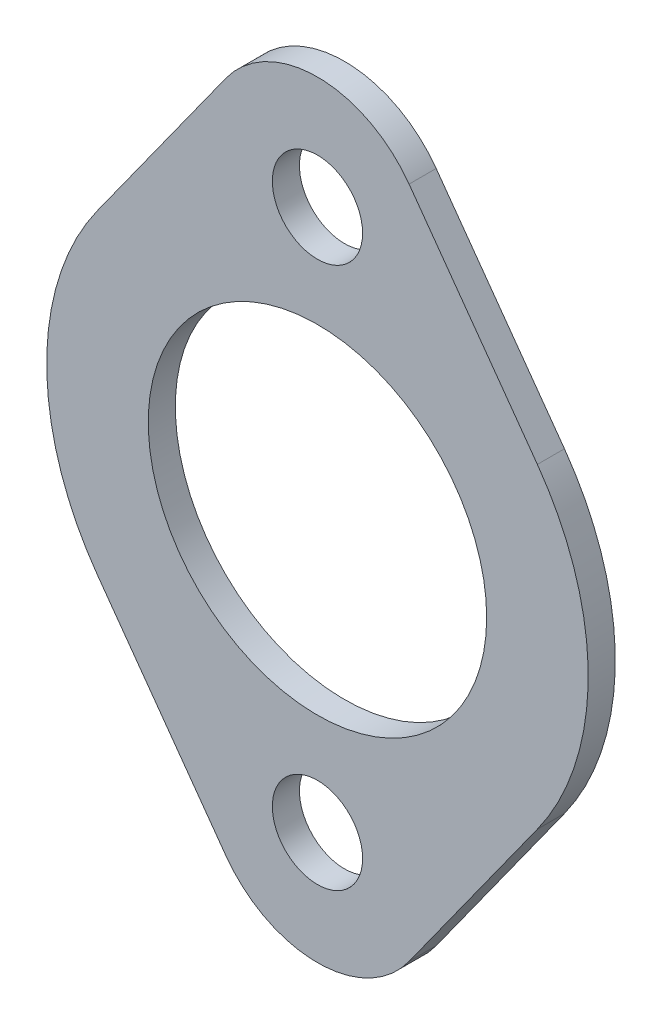
SolidWorks part; units mm, degrees
material "PW20:29:Sc:0:"
ref_plane "Front" through (0, 0, 0) normal (0, 0, 1) x (1, 0, 0)
ref_plane "Top" through (0, 0, 0) normal (0, 1, 0) x (1, 0, 0)
ref_plane "Right" through (0, 0, 0) normal (1, 0, 0) x (0, 0, -1)
sketch "Sketch1" plane through (0, 0, 0) normal (0, 0, 1) x (1, 0, 0)
  line L0 (0, 0) -> (0, 94.4945) construction
  line L1 (0, 0) -> (88.837, 0) construction
  line L2 (12.8942, 47.3604) -> (30.9461, 22.225)
  line L3 (12.8942, -47.3604) -> (30.9461, -22.225)
  line L4 (-12.8942, 47.3604) -> (-30.9461, 22.225)
  line L5 (-12.8942, -47.3604) -> (-30.9461, -22.225)
  arc A0 (-12.8942, 47.3604) -> (12.8942, 47.3604) centre (0, 38.1) cw
  arc A1 (-12.8942, -47.3604) -> (12.8942, -47.3604) centre (0, -38.1) ccw
  arc A2 (30.9461, 22.225) -> (30.9461, -22.225) centre (0, 0) cw
  arc A3 (-30.9461, -22.225) -> (-30.9461, 22.225) centre (0, 0) cw
  dimension "EndR" = 15.875
  dimension "SideR" = 38.1
  dimension "CtoC" = 76.2
extrude "Main" add sketch "Sketch1" along normal blind 3.81
sketch "Sketch2" plane through (0, 0, 3.81) normal (0, 0, 1) x (1, 0, 0)
  circle A0 centre (0, 38.1) radius 6.35
  circle A1 centre (0, -38.1) radius 6.35
  circle A2 centre (0, 0) radius 23.8125
  dimension "BoltH" = 12.7
  dimension "CenterH" = 47.625
extrude "Holes" cut sketch "Sketch2" against normal through all
